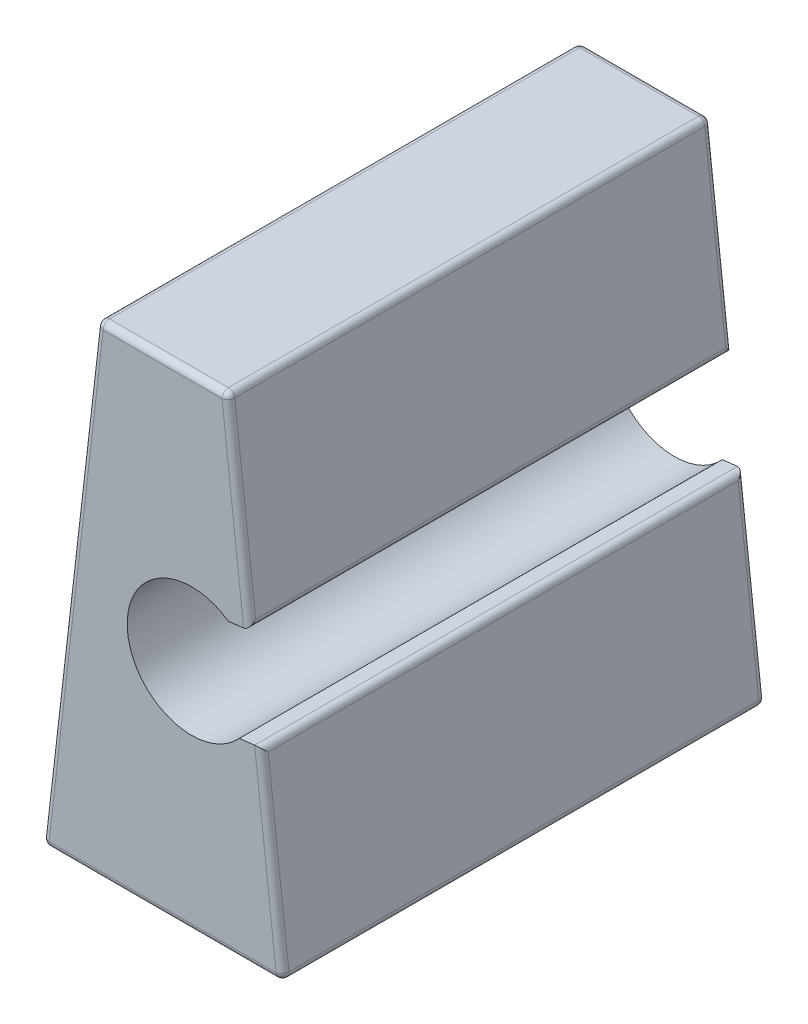
SolidWorks part; units mm, degrees
ref_plane "前视基准面" through (0, 0, 0) normal (0, 0, 1) x (1, 0, 0)
ref_plane "上视基准面" through (0, 0, 0) normal (0, 1, 0) x (1, 0, 0)
ref_plane "右视基准面" through (0, 0, 0) normal (1, 0, 0) x (0, 0, -1)
sketch "草图1" plane through (0, 0, 0) normal (0, 0, 1) x (1, 0, 0)
  line L0 (-3.75, 0) -> (-2.0244, 15)
  line L2 (-3.75, 0) -> (3.75, 0)
  line L3 (3.75, 0) -> (2.0244, 15)
  line L5 (-2.0244, 15) -> (2.0244, 15)
  point P1 (0, 15)
  point P9 (0, 0)
extrude "凸台-拉伸1" add sketch "草图1" along normal blind 15
sketch "草图2" plane through (0, 0, 15) normal (0, 0, 1) x (1, 0, 0)
  line L0 (2.7158, 8.9902) -> (3.0586, 6.0098)
  line L1 (2.7158, 8.9902) -> (2.0431, 8.9128)
  line L2 (3.75, 0) -> (2.0244, 15) construction
  line L4 (3.0586, 6.0098) -> (2.386, 5.9324)
  arc A0 (2.0431, 8.9128) -> (2.386, 5.9324) centre (0.9003, 7.2714) ccw
  point P11 (2.8872, 7.5)
extrude "切除-拉伸1" cut sketch "草图2" against normal blind 15
sketch "草图3" plane through (-3.701, 0.4258, 0) normal (-0.9934, 0.1143, 0) x (0, 0, 1)
  line L5 (6, 5.6209) -> (6, 8.6209)
  line L6 (6, 8.6209) -> (9, 8.6209)
  line L7 (9, 5.6209) -> (9, 8.6209)
  line L8 (6, 5.6209) -> (9, 5.6209)
  point P13 (7.5, 5.6209)
  point P15 (7.5, 8.6209)
  point P16 (9, 7.1209)
  point P17 (6, 7.1209)
extrude "凸台-拉伸2" add sketch "草图3" along normal blind 0.68
sketch "草图4" plane through (0, 0, 6) normal (0, 0, -1) x (-1, 0, 0)
  line L0 (5.5937, 5.8485) -> (4.6555, 5.7406)
  line L3 (5.148, 9.7229) -> (4.2098, 9.615)
  line L4 (5.5937, 5.8485) -> (5.148, 9.7229)
  line L5 (3.7345, 6.085) -> (3.391, 9.0704)
  line L7 (3.3913, 9.0679) -> (3.7342, 6.0875) construction
  arc A0 (4.6555, 5.7406) -> (3.7345, 6.085) centre (4.8741, 7.7286) cw
  arc A1 (4.2098, 9.615) -> (3.391, 9.0704) centre (4.8741, 7.7286) ccw
  point P15 (3.5628, 7.5777)
  point P16 (5.3708, 7.7857)
extrude "凸台-拉伸3" add sketch "草图4" along normal blind 1 and the other way blind 4
sketch "草图5" plane through (0.6424, 5.5841, 0) normal (-0.1143, -0.9934, 0) x (0.9934, -0.1143, 0)
  line L0 (-3.7254, 7.5) -> (-7.5582, 7.5) construction
  line L1 (-3.7254, 15) -> (-3.7254, 0) construction
  line L2 (-6.2254, 9.45) -> (-6.2254, 10)
  line L3 (-6.2254, 10) -> (-4.4054, 10)
  line L4 (-4.4054, 10) -> (-4.4054, 9.0025)
  line L5 (-6.2254, 10) -> (-6.2254, 5) construction
  line L6 (-6.2254, 9.45) -> (-5.281, 9.45)
  line L8 (-6.2254, 5.55) -> (-5.281, 5.55)
  line L9 (-4.4054, 5) -> (-4.4054, 5.9975)
  line L10 (-6.2254, 5) -> (-4.4054, 5)
  line L11 (-6.2254, 5.55) -> (-6.2254, 5)
  arc A0 (-4.4054, 9.0025) -> (-5.281, 9.45) centre (-5.7254, 7.5) ccw
  arc A1 (-4.4054, 5.9975) -> (-5.281, 5.55) centre (-5.7254, 7.5) cw
extrude "切除-拉伸2" cut sketch "草图5" against normal blind 5 and the other way blind 3
fillet "圆角3" radius 0.2 16 edges at (-2.8872, 7.5, 15) (-2.8872, 7.5, 0) (-3.75, 0, 7.5) (0, 0, 15) (0, 0, 0) (3.75, 0, 7.5) (3.4043, 3.0049, 15) (3.0586, 6.0098, 7.5) (3.4043, 3.0049, 0) (2.3701, 11.9951, 0) (2.7158, 8.9902, 7.5) (2.3701, 11.9951, 15) (2.0244, 15, 7.5) (0, 15, 15) (-2.0244, 15, 7.5) (0, 15, 0)
fillet "圆角4" radius 0.1 4 edges at (-5.3708, 7.7857, 9.45) (-5.5937, 5.8485, 7.5) (-5.3708, 7.7857, 5.55) (-5.148, 9.7229, 7.5)
